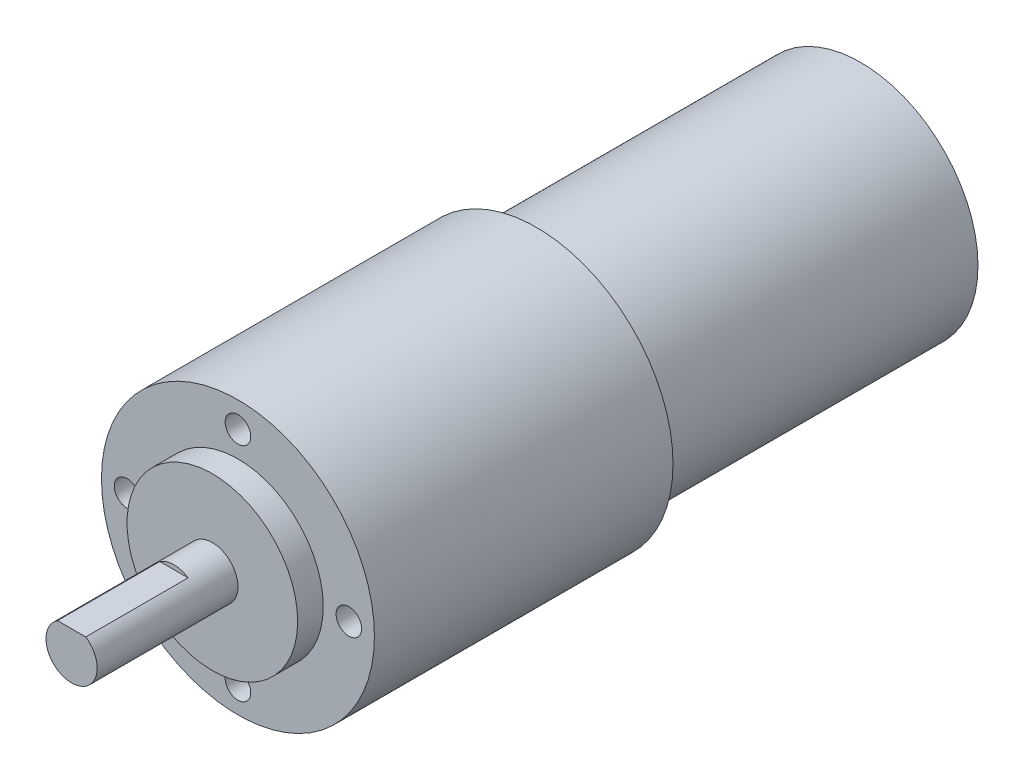
SolidWorks part; units mm, degrees
ref_plane "正面" through (0, 0, 0) normal (0, 0, 1) x (1, 0, 0)
ref_plane "平面" through (0, 0, 0) normal (0, 1, 0) x (1, 0, 0)
ref_plane "右側面" through (0, 0, 0) normal (1, 0, 0) x (0, 0, -1)
sketch "ｽｹｯﾁ1" plane through (0, 0, 0) normal (0, 0, 1) x (1, 0, 0)
  circle A0 centre (0, 0) radius 16
  dimension "D1" = 32
extrude "ﾎﾞｽ - 押し出し1" add sketch "ｽｹｯﾁ1" along normal blind 35
sketch "ｽｹｯﾁ2" plane through (0, 0, 35) normal (0, 0, 1) x (1, 0, 0)
  circle A0 centre (0, 0) radius 10
  dimension "D1" = 20
extrude "ﾎﾞｽ - 押し出し2" add sketch "ｽｹｯﾁ2" along normal blind 3
sketch "ｽｹｯﾁ3" plane through (0, 0, 38) normal (0, 0, 1) x (1, 0, 0)
  circle A0 centre (0, 0) radius 3
  dimension "D1" = 6
extrude "ﾎﾞｽ - 押し出し3" add sketch "ｽｹｯﾁ3" along normal blind 16.5
sketch "ｽｹｯﾁ4" plane through (0, 0, 0) normal (0, 1, 0) x (1, 0, 0)
  line L0 (0, 0) -> (0, -50000) construction
  line L1 (-3, -54.5) -> (3, -54.5) construction
  line L2 (-4.6218, -42.5) -> (4.6218, -42.5)
  line L3 (-4.6218, -42.5) -> (-4.6218, -54.5)
  line L4 (-4.6218, -54.5) -> (4.6218, -54.5)
  line L5 (4.6218, -42.5) -> (4.6218, -54.5)
  line L6 (-4.6218, -42.5) -> (4.6218, -54.5) construction
  line L7 (-4.6218, -54.5) -> (4.6218, -42.5) construction
  point P3 (0, -48.5)
  dimension "D1" = 12
extrude "ｶｯﾄ - 押し出し1" cut sketch "ｽｹｯﾁ4" against normal blind 0.5 from offset 3
sketch "ｽｹｯﾁ5" plane through (0, 0, 0) normal (0, 0, -1) x (-1, 0, 0)
  circle A0 centre (0, 0) radius 13.75
  dimension "D1" = 27.5
extrude "ﾎﾞｽ - 押し出し4" add sketch "ｽｹｯﾁ5" along normal blind 38
sketch "ｽｹｯﾁ6" plane through (0, 0, 35) normal (0, 0, 1) x (1, 0, 0)
  line L0 (0, 0) -> (0, 50000) construction
  line L1 (0, 0) -> (50000, 0) construction
  circle A0 centre (0, 0) radius 13 construction
  circle A1 centre (0, 13) radius 1.5
  circle A2 centre (-13, 0) radius 1.5
  circle A3 centre (13, 0) radius 1.5
  circle A4 centre (0, -13) radius 1.5
  dimension "D1" = 3
  dimension "D2" = 26
extrude "ｶｯﾄ - 押し出し2" cut sketch "ｽｹｯﾁ6" against normal blind 5
